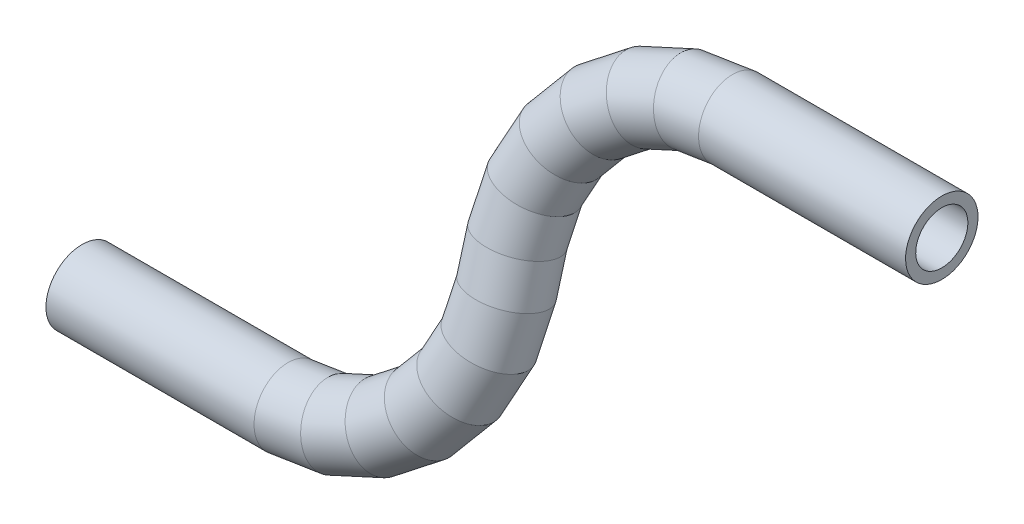
SolidWorks part; units mm, degrees
ref_plane "Front Plane" through (0, 0, 0) normal (0, 0, 1) x (1, 0, 0)
ref_plane "Top Plane" through (0, 0, 0) normal (0, 1, 0) x (1, 0, 0)
ref_plane "Right Plane" through (0, 0, 0) normal (1, 0, 0) x (0, 0, -1)
sketch3d "Path"
  line L0 (-2754.8928, -26.6976, -19.3969) -> (-2773.0928, -26.6976, -19.3969)
  line L1 (-2773.0928, -26.6976, -19.3969) -> (-2776.9751, -27.1901, -19.2604)
  line L2 (-2776.9751, -27.1901, -19.2604) -> (-2780.5928, -28.6342, -18.8601)
  line L3 (-2780.5928, -28.6342, -18.8601) -> (-2783.6994, -30.9313, -18.2234)
  line L4 (-2783.6994, -30.9313, -18.2234) -> (-2786.0832, -33.9251, -17.3936)
  line L5 (-2786.0832, -33.9251, -17.3936) -> (-2787.5817, -37.4113, -16.4273)
  line L6 (-2787.5817, -37.4113, -16.4273) -> (-2788.0928, -41.1526, -15.3903)
  line L7 (-2788.0928, -41.1526, -15.3903) -> (-2788.0928, -44.6335, -14.4255)
  line L8 (-2788.0928, -44.6335, -14.4255) -> (-2788.6039, -48.3747, -13.3885)
  line L9 (-2788.6039, -48.3747, -13.3885) -> (-2790.1024, -51.861, -12.4222)
  line L10 (-2790.1024, -51.861, -12.4222) -> (-2792.4862, -54.8547, -11.5924)
  line L11 (-2792.4862, -54.8547, -11.5924) -> (-2795.5928, -57.1519, -10.9557)
  line L12 (-2795.5928, -57.1519, -10.9557) -> (-2799.2105, -58.5959, -10.5554)
  line L13 (-2799.2105, -58.5959, -10.5554) -> (-2803.0928, -59.0885, -10.4189)
  line L14 (-2803.0928, -59.0885, -10.4189) -> (-2821.2928, -59.0885, -10.4189)
ref_plane "Start Plane" through (-2754.8928, 0, 0) normal (1, 0, 0) x (0, 0, -1)
sketch "Profile" plane through (-2754.8928, 0, 0) normal (1, 0, 0) x (0, 0, -1)
  circle A0 centre (19.3969, -26.6976) radius 3.175
  circle A1 centre (19.3969, -26.6976) radius 2.286
sweep "Tube" add profiles "Profile" path "Path"
